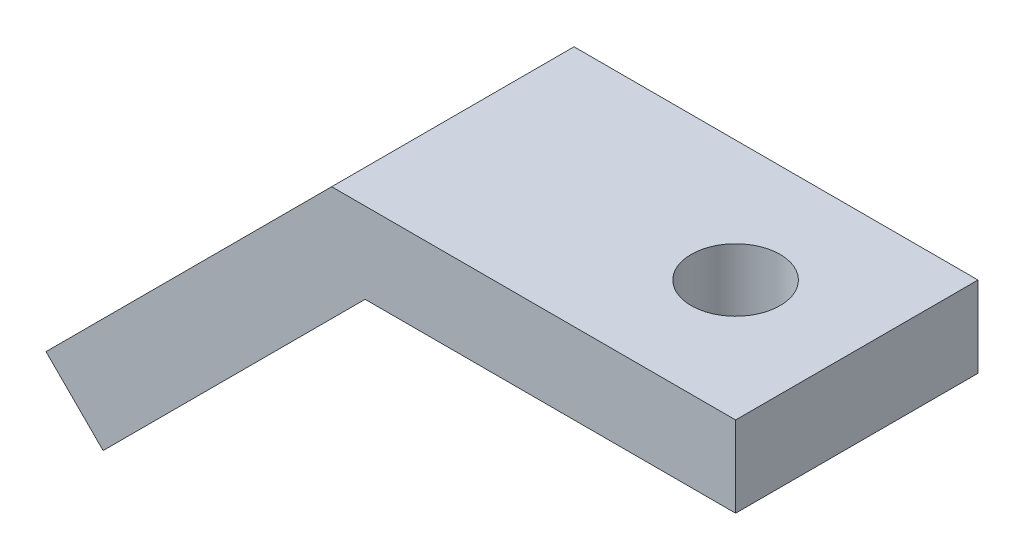
SolidWorks part; units mm, degrees
ref_plane "Front Plane" through (0, 0, 0) normal (0, 0, 1) x (1, 0, 0)
ref_plane "Top Plane" through (0, 0, 0) normal (0, 1, 0) x (1, 0, 0)
ref_plane "Right Plane" through (0, 0, 0) normal (1, 0, 0) x (0, 0, -1)
sketch "Sketch1" plane through (0, 0, 0) normal (0, 0, 1) x (1, 0, 0)
  line L0 (8.6989, 4.3904) -> (-1.3011, 4.3904)
  line L1 (-1.3011, 4.3904) -> (-8.3722, -2.6806)
  line L2 (-8.3722, -2.6806) -> (-6.958, -4.0949)
  line L3 (-6.958, -4.0949) -> (-0.4727, 2.3904)
  line L4 (-0.4727, 2.3904) -> (8.6989, 2.3904)
  line L5 (8.6989, 2.3904) -> (8.6989, 4.3904)
  dimension "D1" = 10
  dimension "D2" = 10
  dimension "D3" = 2
  dimension "D4" = 2
  dimension "D5" = 135
extrude "Boss-Extrude1" add sketch "Sketch1" along normal blind 6
sketch "Sketch2" plane through (0, 4.3904, 0) normal (0, 1, 0) x (1, 0, 0)
  line L0 (8.6989, -6) -> (8.6989, 0) construction
  line L1 (8.6989, 0) -> (-1.3011, 0) construction
  circle A0 centre (5.6989, -3) radius 1.1
  dimension "D1" = 2.2
  dimension "D2" = 3
  dimension "D3" = 3
extrude "Cut-Extrude1" cut sketch "Sketch2" against normal blind 6
sketch "Sketch3" plane through (-2.8458, 2.8458, 0) normal (-0.7071, 0.7071, 0) x (0, 0, 1)
  line L0 (6, 2.1845) -> (6, -7.8155) construction
  line L1 (6, -7.8155) -> (0, -7.8155) construction
  circle A0 centre (3, -4.8155) radius 1.1
  dimension "D1" = 2.2
  dimension "D2" = 3
  dimension "D3" = 3
extrude "Cut-Extrude2" cut sketch "Sketch3" against normal blind 6
